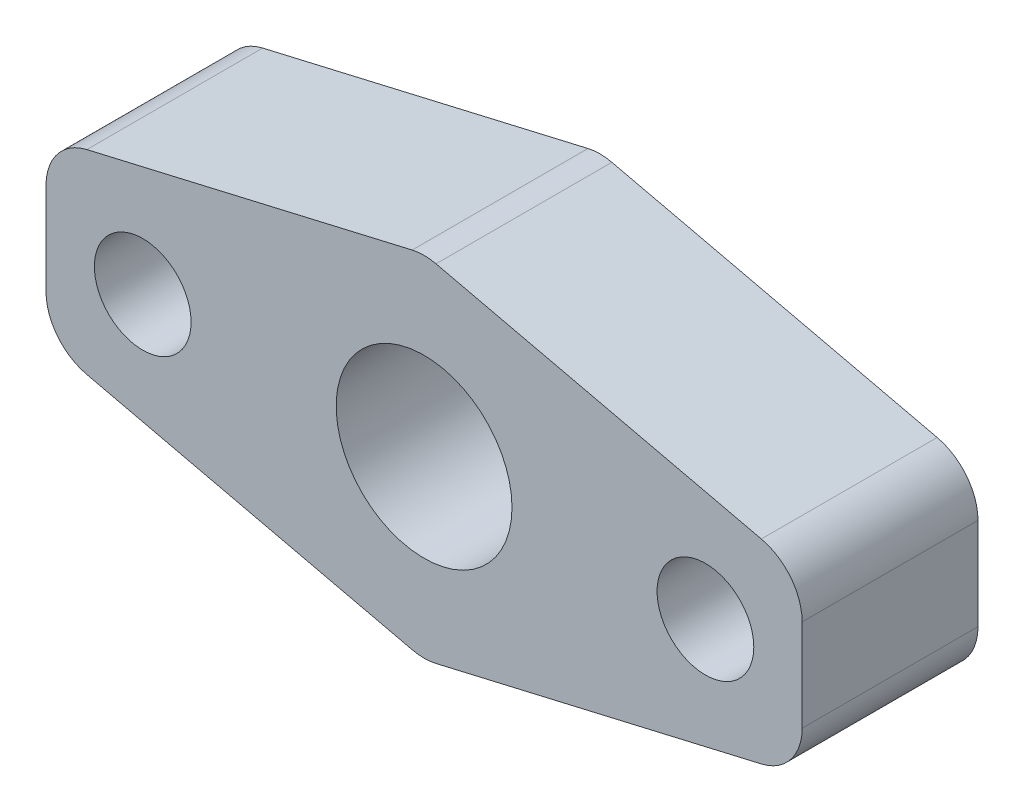
SolidWorks part; units mm, degrees
ref_plane "Front Plane" through (0, 0, 0) normal (0, 0, 1) x (1, 0, 0)
ref_plane "Top Plane" through (0, 0, 0) normal (0, 1, 0) x (1, 0, 0)
ref_plane "Right Plane" through (0, 0, 0) normal (1, 0, 0) x (0, 0, -1)
sketch "Sketch1" plane through (0, 0, 0) normal (0, 0, 1) x (1, 0, 0)
  line L0 (-712.1412, 0) -> (34894.9193, 0) construction
  line L1 (0, -712.1412) -> (0, 34894.9193) construction
  line L3 (-21.5, -5) -> (-21.5, 5)
  line L5 (21.5, -5) -> (21.5, 5)
  line L6 (-21.5, -5) -> (21.5, 5) construction
  line L7 (-21.5, 5) -> (21.5, -5) construction
  line L8 (0, 10) -> (-21.5, 5)
  line L9 (0, 10) -> (21.5, 5)
  line L10 (21.5, -5) -> (0, -10)
  line L11 (0, -10) -> (-21.5, -5)
  circle A0 centre (0, 0) radius 5
  circle A1 centre (-16, 0) radius 2.75
  circle A2 centre (16, 0) radius 2.75
  point P1 (0, 0)
  dimension "D1" = 10
  dimension "D4" = 5.5
  dimension "D2" = 20
  dimension "D3" = 43
  dimension "D5" = 16
  dimension "D6" = 16
  dimension "D7" = 10
extrude "Boss-Extrude1" add sketch "Sketch1" along normal blind 10
fillet "Fillet1" radius 3 6 edges at (0, -10, 5) (-21.5, -5, 5) (-21.5, 5, 5) (21.5, -5, 5) (21.5, 5, 5) (0, 10, 5)
sketch "Sketch2" plane through (0, 0, 0) normal (0, 0, -1) x (-1, 0, 0)
  point P0 (0, 0)
